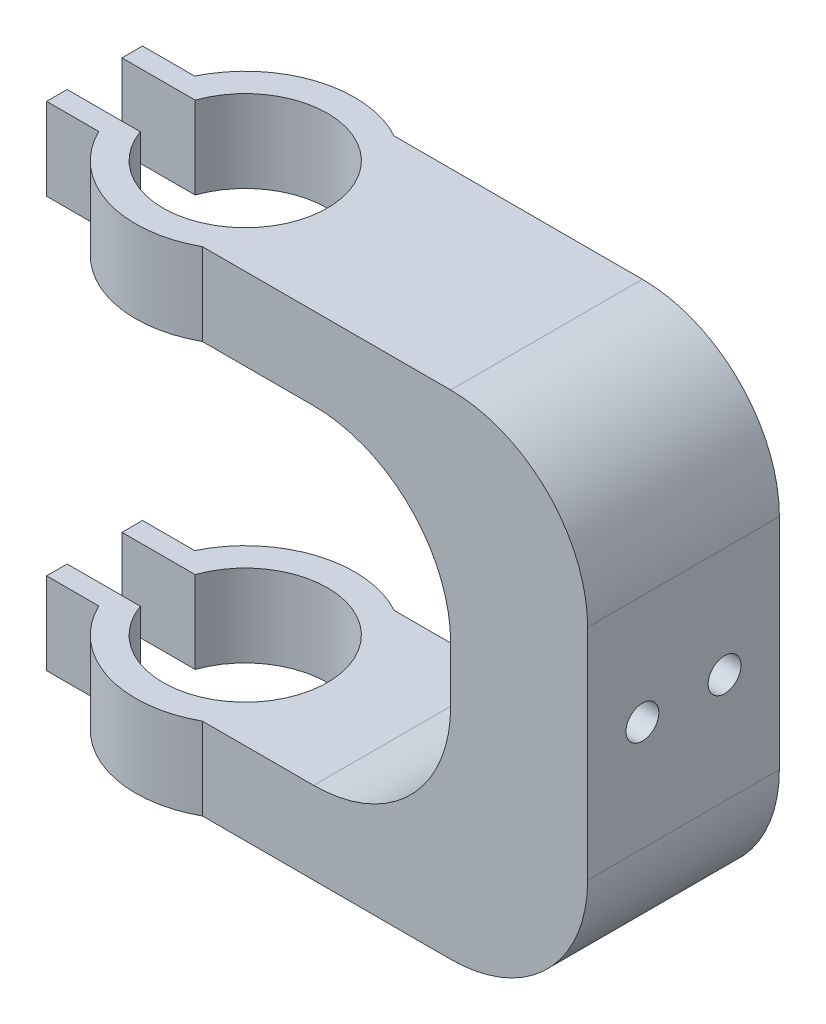
SolidWorks part; units mm, degrees
ref_plane "Front Plane" through (0, 0, 0) normal (0, 0, 1) x (1, 0, 0)
ref_plane "Top Plane" through (0, 0, 0) normal (0, 1, 0) x (1, 0, 0)
ref_plane "Right Plane" through (0, 0, 0) normal (1, 0, 0) x (0, 0, -1)
sketch "Sketch1" plane through (0, 0, 0) normal (0, 0, 1) x (1, 0, 0)
  line L0 (-7.5, 6) -> (-17.5, 6)
  line L5 (-7.5, -6) -> (-17.5, -6)
  line L6 (2.5, 9) -> (-17.5, 9)
  line L10 (-17.5, 9) -> (-17.5, 6)
  line L11 (-4.5761, -9) -> (-17.5, -9)
  line L14 (-17.5, -9) -> (-17.5, -6)
  line L15 (-2.5, 0) -> (2.5, 0) construction
  line L16 (2.5, 9) -> (2.5, -9)
  line L17 (2.5, -9) -> (-4.5761, -9)
  line L18 (-2.5, 1) -> (-2.5, -1)
  arc A0 (-2.5, -1) -> (-7.5, -6) centre (-7.5, -1) cw
  arc A1 (-2.5, 1) -> (-7.5, 6) centre (-7.5, 1) ccw
  point P0 (0, 0)
  point P2 (0, 0)
  point P13 (0, 0)
  point P20 (0, 0)
  dimension "D7" = 5
  dimension "D1" = 18
  dimension "D2" = 20
  dimension "D3" = 20
  dimension "D4" = 3
  dimension "D5" = 3
  dimension "D6" = 5
extrude "Boss-Extrude1" add sketch "Sketch1" along normal mid plane 7
sketch "Sketch2" plane through (-2.5, 0, 0) normal (-1, 0, 0) x (0, 0, 1)
  line L0 (-1.5, 0) -> (1.5, 0) construction
  circle A0 centre (1.5, 0) radius 0.6
  circle A1 centre (-1.5, 0) radius 0.6
  point P4 (0, 0)
  dimension "D2" = 1.2
  dimension "D3" = 1.2
  dimension "D1" = 3
extrude "Cut-Extrude1" cut sketch "Sketch2" against normal through all
sketch "Sketch3" plane through (0, 9, 0) normal (0, 1, 0) x (1, 0, 0)
  line L2 (-17.5, -3.5) -> (-17.5, 3.5) construction
  line L3 (-13.5, 0) -> (2.5, 0) construction
  line L4 (2.5, -3.5) -> (2.5, 3.5) construction
  line L6 (-18.6808, 1) -> (-16.3284, 1)
  line L7 (-18.6808, 1) -> (-18.6808, -1)
  line L8 (-18.6808, -1) -> (-16.3284, -1)
  arc A0 (-16.3284, -1) -> (-16.3284, 1) centre (-13.5, 0) ccw
  circle A1 centre (-13.5, 0) radius 4 construction
  point P12 (0, 0)
  dimension "D1" = 6
  dimension "D2" = 8
  dimension "D3" = 16
  dimension "D4" = 2
extrude "Cut-Extrude2" cut sketch "Sketch3" against normal through all
sketch "Sketch8" plane through (0, 9, 0) normal (0, 1, 0) x (1, 0, 0)
  line L1 (-17.373, 1) -> (-19, 1)
  line L3 (-17.0969, 1.75) -> (-19, 1.75)
  line L4 (-19, 1) -> (-19, 1.75)
  line L5 (-17.373, -1) -> (-19, -1)
  line L7 (-17.0969, -1.75) -> (-19, -1.75)
  line L8 (-19, -1) -> (-19, -1.75)
  circle A0 centre (-13.5, 0) radius 3
  arc A1 (-17.373, 1) -> (-17.373, -1) centre (-13.5, 0) ccw
  arc A2 (-17.0969, -1.75) -> (-17.0969, 1.75) centre (-13.5, 0) ccw
  dimension "D1" = 8
  dimension "D2" = 0.75
  dimension "D3" = 0.75
  dimension "D4" = 5.5
extrude "Boss-Extrude3" add sketch "Sketch8" against normal up to surface (18 mm away)
sketch "Sketch9" plane through (0, 0, -3.5) normal (0, 0, -1) x (-1, 0, 0)
  line L0 (7.5, -6) -> (11.5635, -6) construction
  line L1 (7.5, 6) -> (22.4865, 6)
  line L2 (7.5, 6) -> (7.5, -6)
  line L3 (7.5, -6) -> (22.4865, -6)
  line L4 (22.4865, 6) -> (22.4865, -6)
extrude "Cut-Extrude6" cut sketch "Sketch9" against normal through all and the other way through all
sketch "Sketch10" plane through (0, 9, 0) normal (0, 1, 0) x (1, 0, 0)
  line L0 (-17.5, 1.75) -> (-19, 1.75) construction
  line L3 (-17.5, 1.75) -> (-17.0969, 1.75)
  line L5 (-19, -1.75) -> (-17.5, -1.75) construction
  line L8 (-17.5, -1.75) -> (-17.0969, -1.75)
  line L10 (-15.4365, -3.5) -> (-17.5, -3.5) construction
  line L11 (-17.5, -3.5) -> (-17.5, -1.75) construction
  line L12 (-15.4365, -3.5) -> (-17.5, -3.5)
  line L13 (-17.5, -3.5) -> (-17.5, -1.75)
  line L14 (-15.4365, 3.5) -> (-17.5, 3.5) construction
  line L15 (-17.5, 1.75) -> (-17.5, 3.5) construction
  line L16 (-15.4365, 3.5) -> (-17.5, 3.5)
  line L17 (-17.5, 1.75) -> (-17.5, 3.5)
  line L18 (-17.373, -1) -> (-16.3284, -1)
  line L19 (-17.373, 1) -> (-16.3284, 1)
  arc A0 (-17.0969, -1.75) -> (-15.4365, -3.5) centre (-13.5, 0) ccw
  arc A1 (-15.4365, 3.5) -> (-17.0969, 1.75) centre (-13.5, 0) ccw
  arc A2 (-16.3284, 1) -> (-16.3284, -1) centre (-13.5, 0) ccw
  arc A3 (-17.373, 1) -> (-17.373, -1) centre (-13.5, 0) ccw
extrude "Cut-Extrude8" cut sketch "Sketch10" against normal through all
fillet "Fillet1" radius 5 2 edges at (2.5, -9, 0) (2.5, 9, 0)
